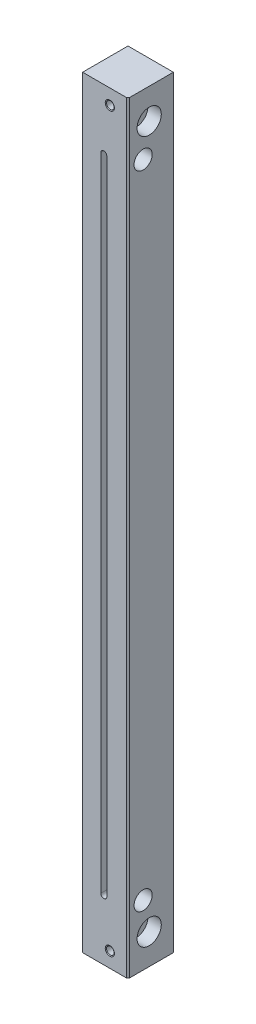
SolidWorks part; units mm, degrees
material "Д16Т ГОСТ 4784-74"
ref_plane "Спереди" through (0, 0, 0) normal (0, 0, 1) x (1, 0, 0)
ref_plane "Сверху" through (0, 0, 0) normal (0, 1, 0) x (1, 0, 0)
ref_plane "Справа" through (0, 0, 0) normal (1, 0, 0) x (0, 0, -1)
sketch "Эскиз1" plane through (0, 0, 0) normal (0, 0, 1) x (1, 0, 0)
  line L1 (0, 0) -> (15, 0)
  line L2 (0, 0) -> (0, 252)
  line L3 (0, 252) -> (15, 252)
  line L4 (15, 0) -> (15, 252)
  dimension "D1" = 15
  dimension "D2" = 252
extrude "Бобышка-Вытянуть1" add sketch "Эскиз1" along normal blind 15
sketch "Эскиз2" plane through (0, 0, 15) normal (0, 0, 1) x (1, 0, 0)
  line L0 (15, 126) -> (0, 126) construction
  line L1 (15, 0) -> (15, 252) construction
  line L2 (0, 252) -> (0, 0) construction
  line L3 (15, 8.5) -> (15, 243.5)
  line L4 (15, 243.5) -> (0, 243.5)
  line L5 (0, 243.5) -> (0, 238.5)
  line L6 (0, 238.5) -> (8, 238.5)
  line L7 (8, 238.5) -> (8, 13.5)
  line L8 (0, 13.5) -> (8, 13.5)
  line L9 (0, 8.5) -> (0, 13.5)
  line L10 (15, 8.5) -> (0, 8.5)
  point P12 (8, 126)
  dimension "D1" = 7
  dimension "D2" = 235
  dimension "D3" = 5
extrude "Бобышка-Вытянуть2" add sketch "Эскиз2" along normal blind 6
sketch "Эскиз3" plane through (0, 0, 15) normal (0, 0, 1) x (1, 0, 0)
  line L0 (8, 13.5) -> (0, 13.5)
  line L1 (8, 13.5) -> (0, 13.5)
  line L2 (8, 238.5) -> (8, 13.5)
  line L3 (8, 238.5) -> (8, 13.5)
  line L4 (0, 15) -> (0, 0)
  line L5 (0, 15) -> (0, 13.5)
  line L6 (0, 238.5) -> (0, 13.5)
  line L7 (0, 238.5) -> (0, 237)
  line L8 (0, 252) -> (0, 237)
  line L11 (0, 238.5) -> (0, 13.5)
  line L14 (0, 238.5) -> (8, 238.5)
  line L15 (0, 238.5) -> (8, 238.5)
extrude "Вырез-Вытянуть1" cut sketch "Эскиз3" against normal through all
sketch "Эскиз7" plane through (0, 243.5, 0) normal (0, 1, 0) x (1, 0, 0)
  line L1 (0, -21) -> (15, -21)
  line L2 (0, -21) -> (0, -15)
  line L3 (0, -15) -> (15, -15)
  line L4 (15, -21) -> (15, -15)
extrude "Вырез-Вытянуть4" cut sketch "Эскиз7" against normal through all
sketch "Эскиз5" plane through (0, 0, 15) normal (0, 0, 1) x (1, 0, 0)
  line L0 (0, 13.5) -> (8, 13.5) construction
  line L1 (0, 13.5) -> (8, 13.5)
  line L2 (0, 13.5) -> (0, 238.5)
  line L3 (0, 238.5) -> (8, 238.5)
  line L4 (8, 13.5) -> (8, 238.5)
  line L5 (0, 252) -> (0, 238.5) construction
  line L6 (8, 238.5) -> (0, 238.5) construction
extrude "Бобышка-Вытянуть3" add sketch "Эскиз5" against normal blind 3
sketch "Эскиз6" plane through (0, 0, 15) normal (0, 0, 1) x (1, 0, 0)
  line L0 (7, 232) -> (7, 20) construction
  line L1 (8, 232) -> (8, 20)
  line L2 (6, 232) -> (6, 20)
  line L3 (8, 13.5) -> (8, 238.5) construction
  line L4 (7, 126) -> (0, 126) construction
  line L5 (0, 252) -> (0, 0) construction
  arc A0 (8, 232) -> (6, 232) centre (7, 232) ccw
  arc A1 (6, 20) -> (8, 20) centre (7, 20) ccw
  point P2 (7, 126)
  dimension "D1" = 2
  dimension "D2" = 212
extrude "Вырез-Вытянуть3" cut sketch "Эскиз6" against normal blind 8
fillet "Скругление1" radius 5 2 edges at (4, 238.5, 12) (4, 13.5, 12)
chamfer "Фаска1" distance 0.5 angle 45 1 edges
hole_wizard "Отверстие обработанное метчиком M31" positions "Эскиз9" profile "Эскиз8" tap size "M3" standard "DIN"
sketch "Эскиз9" plane through (0, 0, 15) normal (0, 0, 1) x (1, 0, 0)
  line L0 (0, 0) -> (14.5, 0) construction
  line L1 (14.5, 252) -> (0, 252) construction
  line L4 (0, 252) -> (0, 0) construction
  point P1 (9, 5)
  point P7 (9, 247)
  dimension "D1" = 5
  dimension "D2" = 5
  dimension "D3" = 9
sketch "Эскиз8" plane through (9, 5, 15) normal (1, 0, 0) x (0, -1, 0)
  line L0 (0, 0) -> (0, 9.2511)
  line L1 (0, 9.2511) -> (1.25, 8.5)
  line L2 (1.25, 8.5) -> (1.25, 0.1588)
  line L3 (1.25, 0.1588) -> (1.525, 0)
  line L5 (1.525, 0) -> (0, 0)
  line L6 (-1.25, 0.1588) -> (-1.525, 0) construction
  line L10 (0, 9.2511) -> (-1.25, 8.5) construction
  line L11 (0, -6.35) -> (0, 107.95) construction
  dimension "Диаметр сверла" = 2.5
  dimension "Глубина сверла" = 8.5
  dimension "Диаметр передней зенковки" = 3.05
  dimension "Угол передней зенковки" = 120
  dimension "Угол заточки сверла" = 118
cosmetic thread "Отверстие резьбы1" parameters "D1"=6, "D2"=3
cosmetic thread "Отверстие резьбы2" parameters "D1"=6, "D2"=3
hole_wizard "Цековка для  винта с внутренним шестигранником M41" positions "Эскиз11" profile "Эскиз10" counterbore size "M4" standard "DIN" end condition through all
sketch "Эскиз11" plane through (15, 0, 0) normal (1, 0, 0) x (0, 0, -1)
  line L0 (-14.5, 252) -> (0, 252) construction
  line L1 (-15, 0) -> (-15, 252) construction
  line L2 (-14.5, 0) -> (0, 0) construction
  point P0 (-8, 10)
  point P1 (-8, 242)
  dimension "D1" = 10
  dimension "D2" = 7
  dimension "D3" = 10
sketch "Эскиз10" plane through (15, 10, 8) normal (0, 1, 0) x (0, 0, -1)
  line L0 (0, 0) -> (0, 15)
  line L1 (0, 15) -> (2.25, 15)
  line L3 (2.25, 15) -> (2.25, 4.4)
  line L4 (2.25, 4.4) -> (4, 4.4)
  line L5 (4, 4.4) -> (4, 0)
  line L7 (4, 0) -> (0, 0)
  line L11 (0, -6.35) -> (0, 107.95) construction
  dimension "Диаметр сквозного отверстия" = 4.5
  dimension "Глубина сквозного отверстия" = 15
  dimension "Диаметр цековки" = 8
  dimension "Глубина цековки" = 4.4
sketch "Эскиз12" plane through (15, 0, 0) normal (1, 0, 0) x (0, 0, -1)
  line L0 (-14.5, 252) -> (0, 252) construction
  line L1 (-15, 0) -> (-15, 252) construction
  line L2 (-14.5, 0) -> (0, 0) construction
  circle A0 centre (-10, 232) radius 3
  circle A1 centre (-10, 20) radius 3
  dimension "D1" = 6
  dimension "D2" = 20
  dimension "D3" = 5
  dimension "D4" = 20
extrude "Вырез-Вытянуть5" cut sketch "Эскиз12" against normal blind 5
chamfer "Фаска2" distance 1 angle 45 1 edges at (8, 126, 0)
hole_wizard "Отверстие обработанное метчиком M21" positions "Эскиз14" profile "Эскиз13" tap size "M2" standard "DIN"
sketch "Эскиз14" plane through (0, 0, 0) normal (0, 0, -1) x (-1, 0, 0)
  line L0 (-12, 201) -> (-12, 151)
  line L1 (-12, 151) -> (-12, 101)
  line L2 (-12, 101) -> (-12, 51)
  line L3 (-12, 51) -> (-12, 0)
  line L4 (0, 0) -> (-15, 0) construction
  line L6 (-12, 201) -> (-12, 252)
  line L7 (-15, 252) -> (0, 252) construction
  line L9 (-15, 0) -> (-15, 252) construction
  point P0 (-12, 101)
  point P1 (-12, 201)
  point P3 (-12, 151)
  point P5 (-12, 51)
  dimension "D1" = 50
  dimension "D2" = 3
sketch "Эскиз13" plane through (12, 101, 0) normal (1, 0, 0) x (0, 1, 0)
  line L0 (0, 0) -> (0, 6.4807)
  line L1 (0, 6.4807) -> (0.8, 6)
  line L2 (0.8, 6) -> (0.8, 0.1299)
  line L3 (0.8, 0.1299) -> (1.025, 0)
  line L5 (1.025, 0) -> (0, 0)
  line L6 (-0.8, 0.1299) -> (-1.025, 0) construction
  line L10 (0, 6.4807) -> (-0.8, 6) construction
  line L11 (0, -6.35) -> (0, 107.95) construction
  dimension "Диаметр сверла" = 1.6
  dimension "Глубина сверла" = 6
  dimension "Диаметр передней зенковки" = 2.05
  dimension "Угол передней зенковки" = 120
  dimension "Угол заточки сверла" = 118
cosmetic thread "Отверстие резьбы3" parameters "D1"=4, "D2"=2
cosmetic thread "Отверстие резьбы4" parameters "D1"=4, "D2"=2
cosmetic thread "Отверстие резьбы5" parameters "D1"=4, "D2"=2
cosmetic thread "Отверстие резьбы6" parameters "D1"=4, "D2"=2
